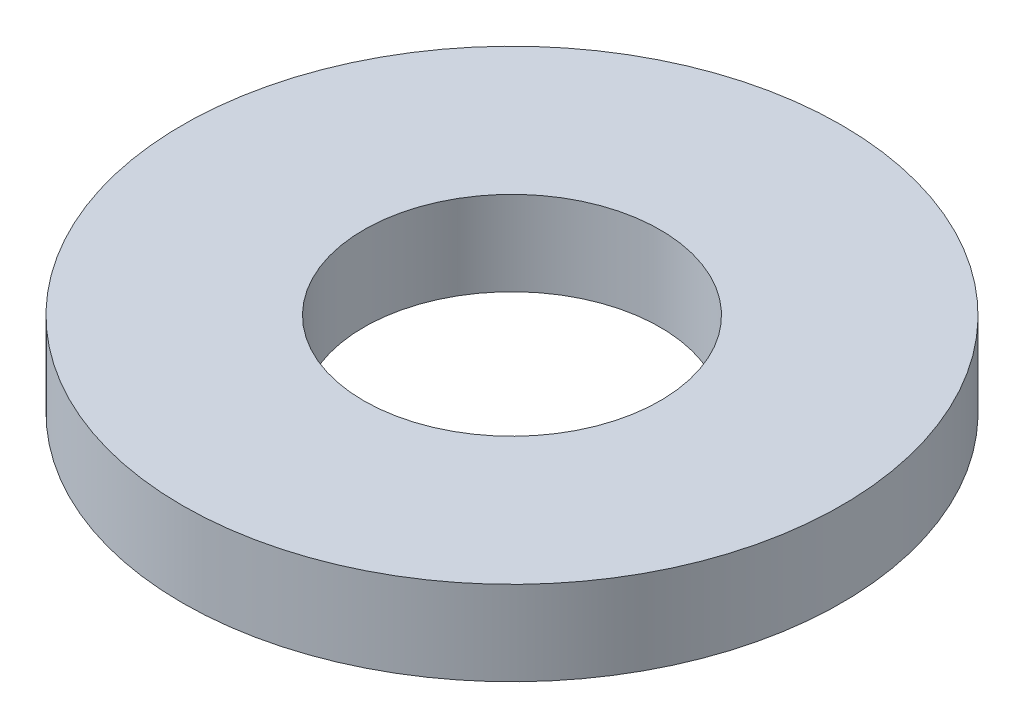
SolidWorks part; units mm, degrees
material "6061-T6 (SS)"
ref_plane "Front Plane" through (0, 0, 0) normal (0, 0, 1) x (1, 0, 0)
ref_plane "Top Plane" through (0, 0, 0) normal (0, 1, 0) x (1, 0, 0)
ref_plane "Right Plane" through (0, 0, 0) normal (1, 0, 0) x (0, 0, -1)
sketch "Sketch1" plane through (0, 0, 0) normal (1, 0, 0) x (0, 0, -1)
  line L0 (0, 19.4356) -> (0, -38.7424) construction
  line L1 (0, 0) -> (3.5687, 0) construction
  line L2 (3.5687, 1.016) -> (7.9375, 1.016)
  line L3 (3.5687, 1.016) -> (3.5687, -1.016)
  line L4 (3.5687, -1.016) -> (7.9375, -1.016)
  line L5 (7.9375, 1.016) -> (7.9375, -1.016)
  dimension "ID" = 7.1374
  dimension "OD" = 15.875
  dimension "height" = 2.032
revolve "Revolve1" add sketch "Sketch1" angle 360 about L0
